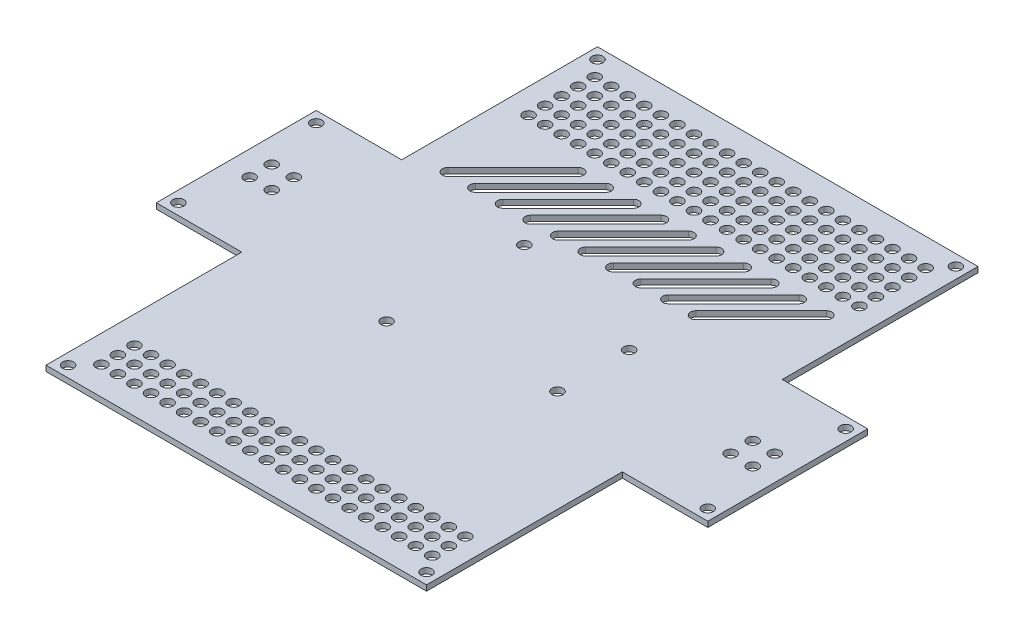
SolidWorks part; units mm, degrees
ref_plane "Front Plane" through (0, 0, 0) normal (0, 0, 1) x (1, 0, 0)
ref_plane "Top Plane" through (0, 0, 0) normal (0, 1, 0) x (1, 0, 0)
ref_plane "Right Plane" through (0, 0, 0) normal (1, 0, 0) x (0, 0, -1)
sketch "Sketch1" plane through (0, 0, 0) normal (0, 1, 0) x (1, 0, 0)
  line L1 (-69, -100) -> (69, -100)
  line L2 (-100, -29) -> (-100, 29)
  line L3 (-69, 100) -> (69, 100)
  line L4 (100, -29) -> (100, 29)
  line L9 (-100, 29) -> (-69, 29)
  line L10 (-69, 100) -> (-69, 29)
  line L12 (-33.182, 57.194) -> (-56.818, 33.558) construction
  line L13 (100, 29) -> (69, 29)
  line L14 (69, 100) -> (69, 29)
  line L15 (-31.7678, 55.7798) -> (-55.4038, 32.1438)
  line L16 (-34.5962, 58.6082) -> (-58.2322, 34.9722)
  line L17 (-100, -29) -> (-69, -29)
  line L18 (-69, -100) -> (-69, -29)
  line L19 (-23.182, 57.194) -> (-46.818, 33.558) construction
  line L20 (-21.7678, 55.7798) -> (-45.4038, 32.1438)
  line L21 (100, -29) -> (69, -29)
  line L22 (69, -100) -> (69, -29)
  line L23 (-24.5962, 58.6082) -> (-48.2322, 34.9722)
  line L24 (-13.182, 57.194) -> (-36.818, 33.558) construction
  line L25 (-11.7678, 55.7798) -> (-35.4038, 32.1438)
  line L26 (-14.5962, 58.6082) -> (-38.2322, 34.9722)
  line L27 (-3.182, 57.194) -> (-26.818, 33.558) construction
  line L28 (-1.7678, 55.7798) -> (-25.4038, 32.1438)
  line L29 (-4.5962, 58.6082) -> (-28.2322, 34.9722)
  line L30 (6.818, 57.194) -> (-16.818, 33.558) construction
  line L31 (8.2322, 55.7798) -> (-15.4038, 32.1438)
  line L32 (5.4038, 58.6082) -> (-18.2322, 34.9722)
  line L33 (16.818, 57.194) -> (-6.818, 33.558) construction
  line L34 (18.2322, 55.7798) -> (-5.4038, 32.1438)
  line L35 (15.4038, 58.6082) -> (-8.2322, 34.9722)
  line L36 (26.818, 57.194) -> (3.182, 33.558) construction
  line L37 (28.2322, 55.7798) -> (4.5962, 32.1438)
  line L38 (25.4038, 58.6082) -> (1.7678, 34.9722)
  line L39 (36.818, 57.194) -> (13.182, 33.558) construction
  line L40 (38.2322, 55.7798) -> (14.5962, 32.1438)
  line L41 (35.4038, 58.6082) -> (11.7678, 34.9722)
  line L42 (46.818, 57.194) -> (23.182, 33.558) construction
  line L43 (48.2322, 55.7798) -> (24.5962, 32.1438)
  line L44 (45.4038, 58.6082) -> (21.7678, 34.9722)
  line L45 (56.818, 57.194) -> (33.182, 33.558) construction
  line L46 (58.2322, 55.7798) -> (34.5962, 32.1438)
  line L47 (55.4038, 58.6082) -> (31.7678, 34.9722)
  circle A0 centre (65, 96) radius 2
  circle A1 centre (-65, 96) radius 2
  circle A2 centre (96, 25) radius 2
  circle A3 centre (96, -25) radius 2
  circle A4 centre (65, -96) radius 2
  circle A5 centre (-65, -96) radius 2
  circle A6 centre (-96, -25) radius 2
  circle A7 centre (-96, 25) radius 2
  circle A8 centre (-60, 90) radius 2
  circle A9 centre (-54, 90) radius 2
  circle A10 centre (-48, 90) radius 2
  circle A11 centre (-42, 90) radius 2
  circle A12 centre (-36, 90) radius 2
  circle A13 centre (-30, 90) radius 2
  circle A14 centre (-24, 90) radius 2
  circle A15 centre (-18, 90) radius 2
  circle A16 centre (-12, 90) radius 2
  circle A17 centre (-6, 90) radius 2
  circle A18 centre (0, 90) radius 2
  circle A19 centre (6, 90) radius 2
  circle A20 centre (12, 90) radius 2
  circle A21 centre (18, 90) radius 2
  circle A22 centre (24, 90) radius 2
  circle A23 centre (30, 90) radius 2
  circle A24 centre (36, 90) radius 2
  circle A25 centre (42, 90) radius 2
  circle A26 centre (48, 90) radius 2
  circle A27 centre (54, 90) radius 2
  circle A28 centre (60, 90) radius 2
  circle A29 centre (-54, 84) radius 2
  circle A30 centre (-48, 84) radius 2
  circle A31 centre (-42, 84) radius 2
  circle A32 centre (-36, 84) radius 2
  circle A33 centre (-30, 84) radius 2
  circle A34 centre (-24, 84) radius 2
  circle A35 centre (-18, 84) radius 2
  circle A36 centre (-12, 84) radius 2
  circle A37 centre (-6, 84) radius 2
  circle A38 centre (0, 84) radius 2
  circle A39 centre (6, 84) radius 2
  circle A40 centre (12, 84) radius 2
  circle A41 centre (18, 84) radius 2
  circle A42 centre (24, 84) radius 2
  circle A43 centre (30, 84) radius 2
  circle A44 centre (36, 84) radius 2
  circle A45 centre (42, 84) radius 2
  circle A46 centre (48, 84) radius 2
  circle A47 centre (54, 84) radius 2
  circle A48 centre (60, 84) radius 2
  circle A49 centre (-54, 78) radius 2
  circle A50 centre (-48, 78) radius 2
  circle A51 centre (-42, 78) radius 2
  circle A52 centre (-36, 78) radius 2
  circle A53 centre (-30, 78) radius 2
  circle A54 centre (-24, 78) radius 2
  circle A55 centre (-18, 78) radius 2
  circle A56 centre (-12, 78) radius 2
  circle A57 centre (-6, 78) radius 2
  circle A58 centre (0, 78) radius 2
  circle A59 centre (6, 78) radius 2
  circle A60 centre (12, 78) radius 2
  circle A61 centre (18, 78) radius 2
  circle A62 centre (24, 78) radius 2
  circle A63 centre (30, 78) radius 2
  circle A64 centre (36, 78) radius 2
  circle A65 centre (42, 78) radius 2
  circle A66 centre (48, 78) radius 2
  circle A67 centre (54, 78) radius 2
  circle A68 centre (60, 78) radius 2
  circle A69 centre (-54, 72) radius 2
  circle A70 centre (-48, 72) radius 2
  circle A71 centre (-42, 72) radius 2
  circle A72 centre (-36, 72) radius 2
  circle A73 centre (-30, 72) radius 2
  circle A74 centre (-24, 72) radius 2
  circle A75 centre (-18, 72) radius 2
  circle A76 centre (-12, 72) radius 2
  circle A77 centre (-6, 72) radius 2
  circle A78 centre (0, 72) radius 2
  circle A79 centre (6, 72) radius 2
  circle A80 centre (12, 72) radius 2
  circle A81 centre (18, 72) radius 2
  circle A82 centre (24, 72) radius 2
  circle A83 centre (30, 72) radius 2
  circle A84 centre (36, 72) radius 2
  circle A85 centre (42, 72) radius 2
  circle A86 centre (48, 72) radius 2
  circle A87 centre (54, 72) radius 2
  circle A88 centre (60, 72) radius 2
  circle A89 centre (-54, 66) radius 2
  circle A90 centre (-48, 66) radius 2
  circle A91 centre (-42, 66) radius 2
  circle A92 centre (-36, 66) radius 2
  circle A93 centre (-30, 66) radius 2
  circle A94 centre (-24, 66) radius 2
  circle A95 centre (-18, 66) radius 2
  circle A96 centre (-12, 66) radius 2
  circle A97 centre (-6, 66) radius 2
  circle A98 centre (0, 66) radius 2
  circle A99 centre (6, 66) radius 2
  circle A100 centre (12, 66) radius 2
  circle A101 centre (18, 66) radius 2
  circle A102 centre (24, 66) radius 2
  circle A103 centre (30, 66) radius 2
  circle A104 centre (36, 66) radius 2
  circle A105 centre (42, 66) radius 2
  circle A106 centre (48, 66) radius 2
  circle A107 centre (54, 66) radius 2
  circle A108 centre (60, 66) radius 2
  arc A113 (-31.7678, 55.7798) -> (-34.5962, 58.6082) centre (-33.182, 57.194) ccw
  arc A114 (-58.2322, 34.9722) -> (-55.4038, 32.1438) centre (-56.818, 33.558) ccw
  arc A115 (-21.7678, 55.7798) -> (-24.5962, 58.6082) centre (-23.182, 57.194) ccw
  arc A116 (-48.2322, 34.9722) -> (-45.4038, 32.1438) centre (-46.818, 33.558) ccw
  arc A117 (-11.7678, 55.7798) -> (-14.5962, 58.6082) centre (-13.182, 57.194) ccw
  arc A118 (-38.2322, 34.9722) -> (-35.4038, 32.1438) centre (-36.818, 33.558) ccw
  arc A119 (-1.7678, 55.7798) -> (-4.5962, 58.6082) centre (-3.182, 57.194) ccw
  arc A120 (-28.2322, 34.9722) -> (-25.4038, 32.1438) centre (-26.818, 33.558) ccw
  arc A121 (8.2322, 55.7798) -> (5.4038, 58.6082) centre (6.818, 57.194) ccw
  arc A122 (-18.2322, 34.9722) -> (-15.4038, 32.1438) centre (-16.818, 33.558) ccw
  arc A123 (18.2322, 55.7798) -> (15.4038, 58.6082) centre (16.818, 57.194) ccw
  arc A124 (-8.2322, 34.9722) -> (-5.4038, 32.1438) centre (-6.818, 33.558) ccw
  arc A125 (28.2322, 55.7798) -> (25.4038, 58.6082) centre (26.818, 57.194) ccw
  arc A126 (1.7678, 34.9722) -> (4.5962, 32.1438) centre (3.182, 33.558) ccw
  arc A127 (38.2322, 55.7798) -> (35.4038, 58.6082) centre (36.818, 57.194) ccw
  arc A128 (11.7678, 34.9722) -> (14.5962, 32.1438) centre (13.182, 33.558) ccw
  arc A129 (48.2322, 55.7798) -> (45.4038, 58.6082) centre (46.818, 57.194) ccw
  arc A130 (21.7678, 34.9722) -> (24.5962, 32.1438) centre (23.182, 33.558) ccw
  arc A131 (58.2322, 55.7798) -> (55.4038, 58.6082) centre (56.818, 57.194) ccw
  arc A132 (31.7678, 34.9722) -> (34.5962, 32.1438) centre (33.182, 33.558) ccw
  circle A149 centre (-53.1471, -77.7712) radius 2
  circle A150 centre (-47.1471, -77.7712) radius 2
  circle A151 centre (-41.1471, -77.7712) radius 2
  circle A152 centre (-35.1471, -77.7712) radius 2
  circle A153 centre (-29.1471, -77.7712) radius 2
  circle A154 centre (-23.1471, -77.7712) radius 2
  circle A155 centre (-17.1471, -77.7712) radius 2
  circle A156 centre (-11.1471, -77.7712) radius 2
  circle A157 centre (-5.1471, -77.7712) radius 2
  circle A158 centre (0.8529, -77.7712) radius 2
  circle A159 centre (6.8529, -77.7712) radius 2
  circle A160 centre (12.8529, -77.7712) radius 2
  circle A161 centre (18.8529, -77.7712) radius 2
  circle A162 centre (24.8529, -77.7712) radius 2
  circle A163 centre (30.8529, -77.7712) radius 2
  circle A164 centre (36.8529, -77.7712) radius 2
  circle A165 centre (42.8529, -77.7712) radius 2
  circle A166 centre (48.8529, -77.7712) radius 2
  circle A167 centre (54.8529, -77.7712) radius 2
  circle A168 centre (60.8529, -77.7712) radius 2
  circle A169 centre (-53.1471, -83.7712) radius 2
  circle A170 centre (-47.1471, -83.7712) radius 2
  circle A171 centre (-41.1471, -83.7712) radius 2
  circle A172 centre (-35.1471, -83.7712) radius 2
  circle A173 centre (-29.1471, -83.7712) radius 2
  circle A174 centre (-23.1471, -83.7712) radius 2
  circle A175 centre (-17.1471, -83.7712) radius 2
  circle A176 centre (-11.1471, -83.7712) radius 2
  circle A177 centre (-5.1471, -83.7712) radius 2
  circle A178 centre (0.8529, -83.7712) radius 2
  circle A179 centre (6.8529, -83.7712) radius 2
  circle A180 centre (12.8529, -83.7712) radius 2
  circle A181 centre (18.8529, -83.7712) radius 2
  circle A182 centre (24.8529, -83.7712) radius 2
  circle A183 centre (30.8529, -83.7712) radius 2
  circle A184 centre (36.8529, -83.7712) radius 2
  circle A185 centre (42.8529, -83.7712) radius 2
  circle A186 centre (48.8529, -83.7712) radius 2
  circle A187 centre (54.8529, -83.7712) radius 2
  circle A188 centre (60.8529, -83.7712) radius 2
  circle A189 centre (-53.1471, -89.7712) radius 2
  circle A190 centre (-47.1471, -89.7712) radius 2
  circle A191 centre (-41.1471, -89.7712) radius 2
  circle A192 centre (-35.1471, -89.7712) radius 2
  circle A193 centre (-29.1471, -89.7712) radius 2
  circle A194 centre (-23.1471, -89.7712) radius 2
  circle A195 centre (-17.1471, -89.7712) radius 2
  circle A196 centre (-11.1471, -89.7712) radius 2
  circle A197 centre (-5.1471, -89.7712) radius 2
  circle A198 centre (0.8529, -89.7712) radius 2
  circle A199 centre (6.8529, -89.7712) radius 2
  circle A200 centre (12.8529, -89.7712) radius 2
  circle A201 centre (18.8529, -89.7712) radius 2
  circle A202 centre (24.8529, -89.7712) radius 2
  circle A203 centre (30.8529, -89.7712) radius 2
  circle A204 centre (36.8529, -89.7712) radius 2
  circle A205 centre (42.8529, -89.7712) radius 2
  circle A206 centre (48.8529, -89.7712) radius 2
  circle A207 centre (54.8529, -89.7712) radius 2
  circle A208 centre (60.8529, -89.7712) radius 2
  circle A209 centre (-60, 84) radius 2
  circle A210 centre (-60, 78) radius 2
  circle A211 centre (-60, 72) radius 2
  circle A212 centre (-60, 66) radius 2
  circle A215 centre (-59.1471, -77.7712) radius 2
  circle A216 centre (-59.1471, -83.7712) radius 2
  circle A217 centre (-59.1471, -89.7712) radius 2
  circle A218 centre (-20, 24.5) radius 2
  circle A219 centre (32, 10.5) radius 2
  circle A220 centre (32, -15.5) radius 2
  circle A221 centre (-21, -24.5) radius 2
  circle A222 centre (-91.102, 3.9629) radius 2
  circle A223 centre (-83.102, 3.9629) radius 2
  circle A224 centre (-91.102, -4.0371) radius 2
  circle A225 centre (-83.102, -4.0371) radius 2
  circle A226 centre (82.9273, 4.3686) radius 2
  circle A227 centre (90.9273, 4.3686) radius 2
  circle A228 centre (82.9273, -3.6314) radius 2
  circle A229 centre (90.9273, -3.6314) radius 2
  circle A230 centre (-54, 60) radius 2 [skipped]
  circle A231 centre (-48, 60) radius 2 [skipped]
  circle A232 centre (-42, 60) radius 2 [skipped]
  circle A233 centre (-36, 60) radius 2 [skipped]
  circle A234 centre (-30, 60) radius 2 [skipped]
  circle A235 centre (-24, 60) radius 2 [skipped]
  circle A236 centre (-18, 60) radius 2 [skipped]
  circle A237 centre (-12, 60) radius 2 [skipped]
  circle A238 centre (-6, 60) radius 2 [skipped]
  circle A239 centre (0, 60) radius 2 [skipped]
  circle A240 centre (6, 60) radius 2 [skipped]
  circle A241 centre (12, 60) radius 2 [skipped]
  circle A242 centre (18, 60) radius 2 [skipped]
  circle A243 centre (24, 60) radius 2 [skipped]
  circle A244 centre (30, 60) radius 2 [skipped]
  circle A245 centre (36, 60) radius 2 [skipped]
  circle A246 centre (42, 60) radius 2 [skipped]
  circle A247 centre (48, 60) radius 2 [skipped]
  circle A248 centre (54, 60) radius 2 [skipped]
  circle A249 centre (60, 60) radius 2 [skipped]
  circle A250 centre (-54, 54) radius 2 [skipped]
  circle A251 centre (-48, 54) radius 2 [skipped]
  circle A252 centre (-42, 54) radius 2 [skipped]
  circle A253 centre (-36, 54) radius 2 [skipped]
  circle A254 centre (-30, 54) radius 2 [skipped]
  circle A255 centre (-24, 54) radius 2 [skipped]
  circle A256 centre (-18, 54) radius 2 [skipped]
  circle A257 centre (-12, 54) radius 2 [skipped]
  circle A258 centre (-6, 54) radius 2 [skipped]
  circle A259 centre (0, 54) radius 2 [skipped]
  circle A260 centre (6, 54) radius 2 [skipped]
  circle A261 centre (12, 54) radius 2 [skipped]
  circle A262 centre (18, 54) radius 2 [skipped]
  circle A263 centre (24, 54) radius 2 [skipped]
  circle A264 centre (30, 54) radius 2 [skipped]
  circle A265 centre (36, 54) radius 2 [skipped]
  circle A266 centre (42, 54) radius 2 [skipped]
  circle A267 centre (48, 54) radius 2 [skipped]
  circle A268 centre (54, 54) radius 2 [skipped]
  circle A269 centre (60, 54) radius 2 [skipped]
  circle A270 centre (-54, 48) radius 2 [skipped]
  circle A271 centre (-48, 48) radius 2 [skipped]
  circle A272 centre (-42, 48) radius 2 [skipped]
  circle A273 centre (-36, 48) radius 2 [skipped]
  circle A274 centre (-30, 48) radius 2 [skipped]
  circle A275 centre (-24, 48) radius 2 [skipped]
  circle A276 centre (-18, 48) radius 2 [skipped]
  circle A277 centre (-12, 48) radius 2 [skipped]
  circle A278 centre (-6, 48) radius 2 [skipped]
  circle A279 centre (0, 48) radius 2 [skipped]
  circle A280 centre (6, 48) radius 2 [skipped]
  circle A281 centre (12, 48) radius 2 [skipped]
  circle A282 centre (18, 48) radius 2 [skipped]
  circle A283 centre (24, 48) radius 2 [skipped]
  circle A284 centre (30, 48) radius 2 [skipped]
  circle A285 centre (36, 48) radius 2 [skipped]
  circle A286 centre (42, 48) radius 2 [skipped]
  circle A287 centre (48, 48) radius 2 [skipped]
  circle A288 centre (54, 48) radius 2 [skipped]
  circle A289 centre (60, 48) radius 2 [skipped]
  circle A290 centre (-54, 42) radius 2 [skipped]
  circle A291 centre (-48, 42) radius 2 [skipped]
  circle A292 centre (-42, 42) radius 2 [skipped]
  circle A293 centre (-36, 42) radius 2 [skipped]
  circle A294 centre (-30, 42) radius 2 [skipped]
  circle A295 centre (-24, 42) radius 2 [skipped]
  circle A296 centre (-18, 42) radius 2 [skipped]
  circle A297 centre (-12, 42) radius 2 [skipped]
  circle A298 centre (-6, 42) radius 2 [skipped]
  circle A299 centre (0, 42) radius 2 [skipped]
  circle A300 centre (6, 42) radius 2 [skipped]
  circle A301 centre (12, 42) radius 2 [skipped]
  circle A302 centre (18, 42) radius 2 [skipped]
  circle A303 centre (24, 42) radius 2 [skipped]
  circle A304 centre (30, 42) radius 2 [skipped]
  circle A305 centre (36, 42) radius 2 [skipped]
  circle A306 centre (42, 42) radius 2 [skipped]
  circle A307 centre (48, 42) radius 2 [skipped]
  circle A308 centre (54, 42) radius 2 [skipped]
  circle A309 centre (60, 42) radius 2 [skipped]
  circle A310 centre (-54, 36) radius 2 [skipped]
  circle A311 centre (-48, 36) radius 2 [skipped]
  circle A312 centre (-42, 36) radius 2 [skipped]
  circle A313 centre (-36, 36) radius 2 [skipped]
  circle A314 centre (-30, 36) radius 2 [skipped]
  circle A315 centre (-24, 36) radius 2 [skipped]
  circle A316 centre (-18, 36) radius 2 [skipped]
  circle A317 centre (-12, 36) radius 2 [skipped]
  circle A318 centre (-6, 36) radius 2 [skipped]
  circle A319 centre (0, 36) radius 2 [skipped]
  circle A320 centre (6, 36) radius 2 [skipped]
  circle A321 centre (12, 36) radius 2 [skipped]
  circle A322 centre (18, 36) radius 2 [skipped]
  circle A323 centre (24, 36) radius 2 [skipped]
  circle A324 centre (30, 36) radius 2 [skipped]
  circle A325 centre (36, 36) radius 2 [skipped]
  circle A326 centre (42, 36) radius 2 [skipped]
  circle A327 centre (48, 36) radius 2 [skipped]
  circle A328 centre (54, 36) radius 2 [skipped]
  circle A329 centre (-60, 60) radius 2 [skipped]
  circle A330 centre (-60, 54) radius 2 [skipped]
  circle A331 centre (-60, 48) radius 2 [skipped]
  circle A332 centre (-60, 42) radius 2 [skipped]
  circle A333 centre (60, 36) radius 2 [skipped]
  circle A334 centre (-60, 36) radius 2 [skipped]
  point P0 (0, 0)
  point P2 (100, 0)
  point P3 (-87.066, 0)
  point P4 (0, 0)
  point P18 (0, 0)
  point P32 (0, 0)
  point P239 (0, 0)
  point P251 (-45, 45.376)
  point P259 (-35, 45.376)
  point P266 (-25, 45.376)
  point P273 (-15, 45.376)
  point P280 (-5, 45.376)
  point P287 (5, 45.376)
  point P294 (15, 45.376)
  point P301 (25, 45.376)
  point P308 (35, 45.376)
  point P315 (45, 45.376)
  point P457 (87.066, 0)
  dimension "D2" = 4
  dimension "D11" = 4
  dimension "D12" = 4
  dimension "D13" = 4
  dimension "D14" = 4
  dimension "D16" = 4
  dimension "D19" = 4
  dimension "D21" = 4
  dimension "D24" = 4
  dimension "D26" = 4
  dimension "D28" = 4
  dimension "D30" = 10
  dimension "D34" = 4
  dimension "D39" = 12.934
  dimension "D41" = 12.934
  dimension "D43" = 138
  dimension "D37" = 58
  dimension "D38" = 29
  dimension "D40" = 29
  dimension "D35" = 10
  dimension "D3" = 31
  dimension "D4" = 71
  dimension "D5" = 31
  dimension "D6" = 71
  dimension "D7" = 71
  dimension "D8" = 31
  dimension "D9" = 31
  dimension "D10" = 71
  dimension "D15" = 4
  dimension "D17" = 4
  dimension "D18" = 4
  dimension "D20" = 4
  dimension "D22" = 4
  dimension "D23" = 4
  dimension "D25" = 4
  dimension "D27" = 4
  dimension "D29" = 4
  dimension "D31" = 9
  dimension "D36" = 24
  dimension "D42" = 24
  dimension "D32" = 21
  dimension "D33" = 10
extrude "Boss-Extrude1" add sketch "Sketch1" along normal blind 2
